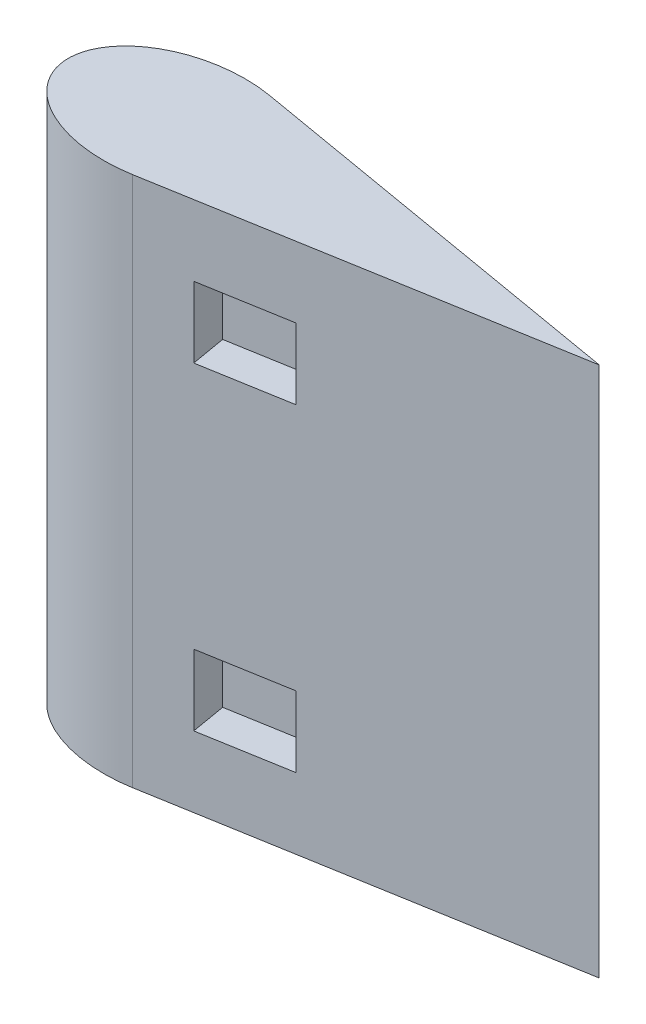
SolidWorks part; units mm, degrees
ref_plane "Front Plane" through (0, 0, 0) normal (0, 0, 1) x (1, 0, 0)
ref_plane "Top Plane" through (0, 0, 0) normal (0, 1, 0) x (1, 0, 0)
ref_plane "Right Plane" through (0, 0, 0) normal (1, 0, 0) x (0, 0, -1)
sketch "Sketch1" plane through (0, 0, 0) normal (0, 1, 0) x (1, 0, 0)
  line L3 (150, 0) -> (37.5, 19.3649)
  line L4 (150, 0) -> (37.5, -19.3649)
  ellipse E0 centre (30, 0) end of major axis (0, 0) minor radius 20 (37.5, 19.3649) -> (37.5, -19.3649) ccw
  dimension "D1" = 40
  dimension "D2" = 30
  dimension "D3" = 114.1545
  dimension "D4" = 19.534
extrude "Boss-Extrude2" add sketch "Sketch1" along normal blind 150
sketch "Sketch11" plane through (0, 0, 0) normal (1, 0, 0) x (0, 0, -1)
  line L0 (16.5511, 150.097) -> (15.0038, 145.9305)
  line L1 (15.0038, 145.9305) -> (16.8749, 141.8488)
  line L2 (16.8749, 141.8488) -> (15.9394, 139.3296)
  line L3 (15.9394, 139.3296) -> (15.9394, 134.0843)
  line L4 (15.9394, 134.0843) -> (15.9394, 130.0301)
  line L5 (15.9394, 130.0301) -> (15.0038, 130.0301)
  line L6 (15.0038, 130.0301) -> (15.0038, 122.4455)
  line L7 (15.0038, 122.4455) -> (15.0038, 115.6227)
  line L8 (15.0038, 115.6227) -> (12.0018, 115.6227)
  line L9 (12.0018, 115.6227) -> (9.5251, 108.9537)
  line L10 (9.5251, 108.9537) -> (12.0018, 103.551)
  line L11 (12.0018, 103.551) -> (15.0038, 97.002)
  line L12 (15.0038, 97.002) -> (15.0038, 91.7159)
  line L13 (15.0038, 91.7159) -> (13.5028, 87.674)
  line L14 (13.5028, 87.674) -> (13.5028, 79.8493)
  line L15 (13.5028, 79.8493) -> (13.5028, 73.2272)
  line L16 (13.5028, 73.2272) -> (13.5028, 70.2579)
  line L17 (13.5028, 70.2579) -> (15.0038, 61.5341)
  line L18 (15.0038, 61.5341) -> (15.0038, 58.7179)
  line L19 (15.0038, 58.7179) -> (15.0038, 52.123)
  line L20 (15.0038, 52.123) -> (12.0018, 51.6065)
  line L21 (12.0018, 51.6065) -> (12.0018, 46.1912)
  line L22 (12.0018, 46.1912) -> (12.9664, 40.5848)
  line L23 (12.9664, 40.5848) -> (13.5028, 38.8652)
  line L24 (13.5028, 38.8652) -> (16.8749, 28.055)
  line L25 (16.8749, 28.055) -> (16.8749, 26.1416)
  line L26 (16.8749, 26.1416) -> (15.1888, 21.6014)
  line L27 (15.1888, 21.6014) -> (13.5028, 21.6014)
  line L28 (13.5028, 21.6014) -> (15.1888, 11.8022)
  line L29 (15.1888, 11.8022) -> (15.1888, 7.8943)
  line L30 (15.1888, 7.8943) -> (13.5028, 7.3683)
  line L31 (13.5028, 7.3683) -> (12.0018, 7.3683)
  line L32 (12.0018, 7.3683) -> (7.7732, 3.1398)
  line L33 (7.7732, 3.1398) -> (9.8875, 3.1398)
  line L34 (9.8875, 3.1398) -> (7.7732, 1.9181)
  line L35 (7.7732, 1.9181) -> (4.7256, 1.9181)
  line L36 (4.7256, 1.9181) -> (-4.2537, 3.1398)
  line L37 (-4.2537, 3.1398) -> (-4.2537, 5.2541)
  line L38 (-4.2537, 5.2541) -> (-6.9084, 9.8483)
  line L39 (-6.9084, 9.8483) -> (-11.4627, 7.2166)
  line L40 (-11.4627, 7.2166) -> (-13.9547, 7.2166)
  line L41 (-13.9547, 7.2166) -> (-15.3851, 11.8022)
  line L42 (-15.3851, 11.8022) -> (-15.3851, 14.0045)
  line L43 (-15.3851, 14.0045) -> (-16.9808, 19.1198)
  line L44 (-16.9808, 19.1198) -> (-18.4148, 21.6014)
  line L45 (-18.4148, 21.6014) -> (-16.3734, 27.0983)
  line L46 (-16.3734, 27.0983) -> (-14.8982, 37.9409)
  line L47 (-14.8982, 37.9409) -> (-16.8018, 41.2353)
  line L48 (-16.8018, 41.2353) -> (-16.8018, 48.8988)
  line L49 (-16.8018, 48.8988) -> (-14.8982, 54.0249)
  line L50 (-14.8982, 54.0249) -> (-12.7087, 59.9206)
  line L51 (-12.7087, 59.9206) -> (-17.0534, 61.5341)
  line L52 (-17.0534, 61.5341) -> (-17.0534, 65.896)
  line L53 (-17.0534, 65.896) -> (-17.0534, 71.7426)
  line L54 (-17.0534, 71.7426) -> (-15.2724, 76.5382)
  line L55 (-15.2724, 76.5382) -> (-17.0696, 82.2995)
  line L56 (-17.0696, 82.2995) -> (-17.0696, 87.674)
  line L57 (-17.0696, 87.674) -> (-17.0696, 91.7159)
  line L58 (-17.0696, 91.7159) -> (-13.9547, 93.5158)
  line L59 (-13.9547, 93.5158) -> (-13.9547, 102.47)
  line L60 (-17.0696, 108.9537) -> (-13.9547, 102.47)
  line L61 (-15.5121, 112.0126) -> (-13.9547, 113.57)
  line L62 (-13.9547, 113.57) -> (-13.9547, 120.4271)
  line L63 (-13.9547, 120.4271) -> (-17.0696, 123.542)
  line L64 (-17.0696, 123.542) -> (-17.0696, 130.0301)
  line L65 (-17.0696, 130.0301) -> (-14.8326, 132.2671)
  line L66 (-14.8326, 132.2671) -> (-14.8326, 137.2969)
  line L67 (-14.8326, 137.2969) -> (-14.8326, 139.3296)
  line L68 (-14.8326, 139.3296) -> (-14.8326, 144.7149)
  line L69 (-14.8326, 144.7149) -> (-12.7087, 144.7149)
  line L70 (-12.7087, 144.7149) -> (-9.8344, 147.5892)
  line L71 (-9.8344, 147.5892) -> (-6.9084, 147.5892)
  line L72 (-6.9084, 147.5892) -> (-2.454, 147.5892)
  line L73 (-2.454, 147.5892) -> (2.2037, 147.5892)
  line L74 (2.2037, 147.5892) -> (3.469, 150.097)
  line L75 (3.469, 150.097) -> (6.0855, 150.097)
  line L76 (6.0855, 150.097) -> (9.5251, 150.097)
  line L77 (9.5251, 150.097) -> (16.5511, 150.097)
  line L78 (-15.5121, 112.0126) -> (-17.0696, 108.9537)
  circle A0 centre (17.545, 108.1308) radius 2
  circle A1 centre (17.5851, 80.961) radius 2
  circle A2 centre (-18.4312, 98.729) radius 2
  circle A3 centre (17.6906, 60.6834) radius 2
  circle A4 centre (20.003, 46.2223) radius 2
  circle A5 centre (-19.0806, 50.0784) radius 2
  circle A6 centre (-18.0011, 142.0878) radius 2
sketch "Sketch12" plane through (4.3165, 0, 25.0769) normal (0.1696, 0, 0.9855) x (0.9855, 0, -0.1696)
  line L0 (33.6715, 75) -> (48.6715, 75) construction
  line L1 (33.6715, 150) -> (33.6715, 0) construction
  line L2 (48.6715, 75) -> (48.6715, 130) construction
  line L3 (48.6715, 75) -> (48.6715, 20) construction
  line L4 (48.6715, 130) -> (73.6715, 130)
  line L9 (73.6715, 130) -> (73.6716, 130)
  line L10 (73.6716, 130) -> (73.6716, 110)
  line L11 (73.6716, 110) -> (48.6715, 110)
  line L12 (48.6715, 110) -> (48.6715, 130)
  line L13 (48.6715, 20) -> (73.6715, 20)
  line L19 (73.6715, 20) -> (73.6715, 40)
  line L20 (73.6715, 40) -> (48.6715, 40)
  line L21 (48.6715, 40) -> (48.6715, 20)
extrude "Cut-Extrude1" cut sketch "Sketch12" against normal blind 10
